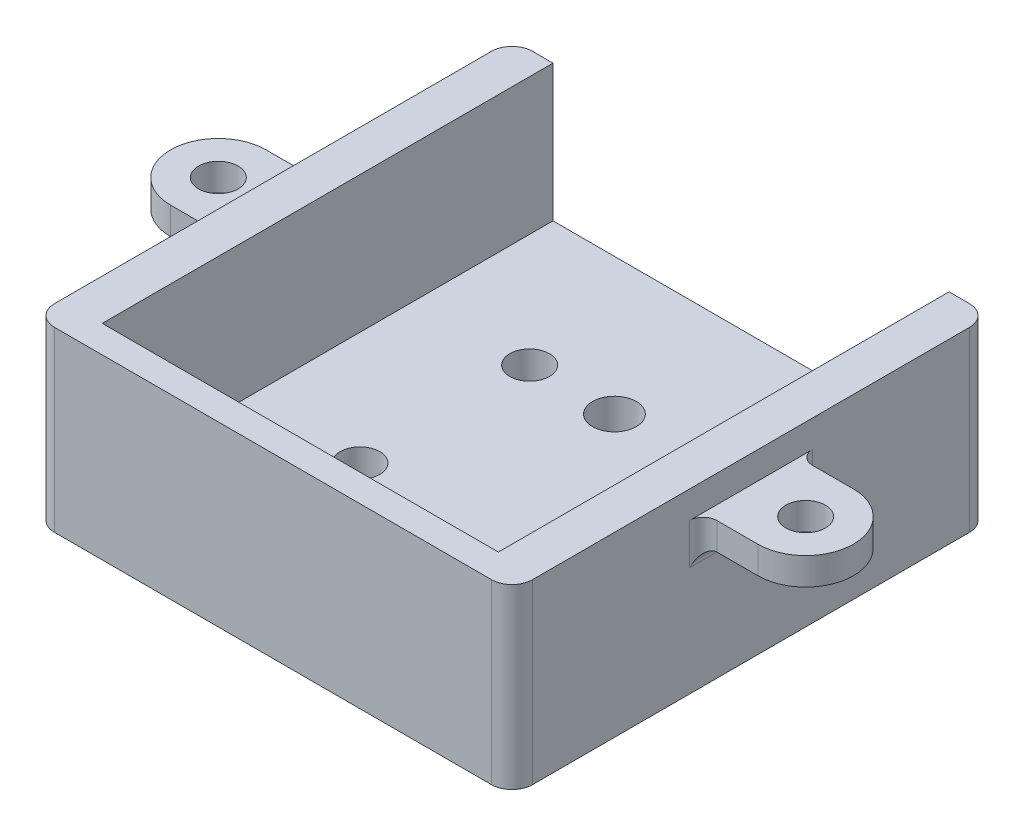
SolidWorks part; units mm, degrees
ref_plane "Front Plane" through (0, 0, 0) normal (0, 0, 1) x (1, 0, 0)
ref_plane "Top Plane" through (0, 0, 0) normal (0, 1, 0) x (1, 0, 0)
ref_plane "Right Plane" through (0, 0, 0) normal (1, 0, 0) x (0, 0, -1)
sketch "Sketch1" plane through (0, 0, 0) normal (0, 1, 0) x (1, 0, 0)
  line L0 (-17.5, -17.5) -> (17.5, -17.5)
  line L1 (17.5, -17.5) -> (17.5, 17.5)
  line L2 (17.5, 17.5) -> (-17.5, 17.5)
  line L3 (-17.5, 17.5) -> (-17.5, -17.5)
  circle A0 centre (6.21, 7.5) radius 1.45
  circle A1 centre (0, 7.5) radius 1.6
  circle A2 centre (-6.21, 7.5) radius 1.45
  circle A3 centre (-6.21, -4.92) radius 1.45
  circle A4 centre (6.21, -4.92) radius 1.45
  circle A5 centre (-6.21, -12.5) radius 1.6
  circle A6 centre (6.21, -12.5) radius 1.6
  dimension "D2" = 2.9
  dimension "D9" = 3.2
  dimension "D1" = 12.42
  dimension "D3" = 10
  dimension "D4" = 35
  dimension "D5" = 35
  dimension "D6" = 10
  dimension "D7" = 5
  dimension "D8" = 17.5
  dimension "D10" = 12.42
  dimension "D11" = 6.21
  dimension "D12" = 11.29
  dimension "D13" = 11.29
  dimension "D14" = 11.29
  dimension "D15" = 11.29
  dimension "D16" = 11.29
  dimension "D17" = 11.29
extrude "Boss-Extrude1" add sketch "Sketch1" along normal blind 13
shell "Shell1" thickness 3
sketch "Sketch2" plane through (0, 13, 0) normal (0, 1, 0) x (1, 0, 0)
  line L0 (14.5, -14.5) -> (14.5, 14.5) construction
  line L1 (-14.5, -15.5) -> (14.5, -15.5)
  line L2 (-14.5, -15.5) -> (-14.5, 25.0232)
  line L3 (-14.5, 25.0232) -> (14.5, 25.0232)
  line L4 (14.5, -15.5) -> (14.5, 25.0232)
  line L5 (-14.5, 14.5) -> (-14.5, -14.5) construction
  line L6 (-14.5, -14.5) -> (-10.3525, -14.5) construction
  dimension "D1" = 1
extrude "Cut-Extrude1" cut sketch "Sketch2" against normal blind 10 contours L2 L1 L4 L3
fillet "Fillet1" radius 1.5 4 edges at (17.5, 6.5, -17.5) (-17.5, 6.5, -17.5) (-17.5, 6.5, 17.5) (17.5, 6.5, 17.5)
ref_plane "Plane1" through (0, 11, 0) normal (0, 1, 0) x (1, 0, 0)
sketch "Sketch4" plane through (0, 11, 0) normal (0, 1, 0) x (1, 0, 0)
  line L0 (-18.2796, 0) -> (-21.5, 0) construction
  line L1 (-17.5, -3.5) -> (-21.5, -3.5)
  line L2 (-17.5, 3.5) -> (-21.5, 3.5)
  line L3 (18.2796, 0) -> (21.5, 0) construction
  line L4 (17.5, 3.5) -> (21.5, 3.5)
  line L5 (17.5, -3.5) -> (21.5, -3.5)
  line L6 (-17.5, 3.5) -> (-17.5, -3.5)
  line L7 (17.5, 3.5) -> (17.5, -3.5)
  line L8 (-17.5, 16) -> (-17.5, -16) construction
  line L9 (17.5, -16) -> (17.5, 16) construction
  arc A0 (-21.5, 3.5) -> (-21.5, -3.5) centre (-21.5, 0) ccw
  arc A1 (21.5, -3.5) -> (21.5, 3.5) centre (21.5, 0) ccw
  circle A2 centre (-21.5, 0) radius 1.45
  circle A3 centre (21.5, 0) radius 1.45
  point P2 (-19.4893, 0)
  point P7 (19.5107, 0)
  dimension "D2" = 2.9
  dimension "D5" = 3.5
  dimension "D1" = 4
  dimension "D3" = 7
  dimension "D4" = 4
extrude "Boss-Extrude3" add sketch "Sketch4" against normal blind 2
fillet "Fillet2" radius 1 6 edges at (-17.5, 10, 3.5) (-17.5, 9, 0) (-17.5, 10, -3.5) (17.5, 10, 3.5) (17.5, 10, -3.5) (17.5, 9, 0)
